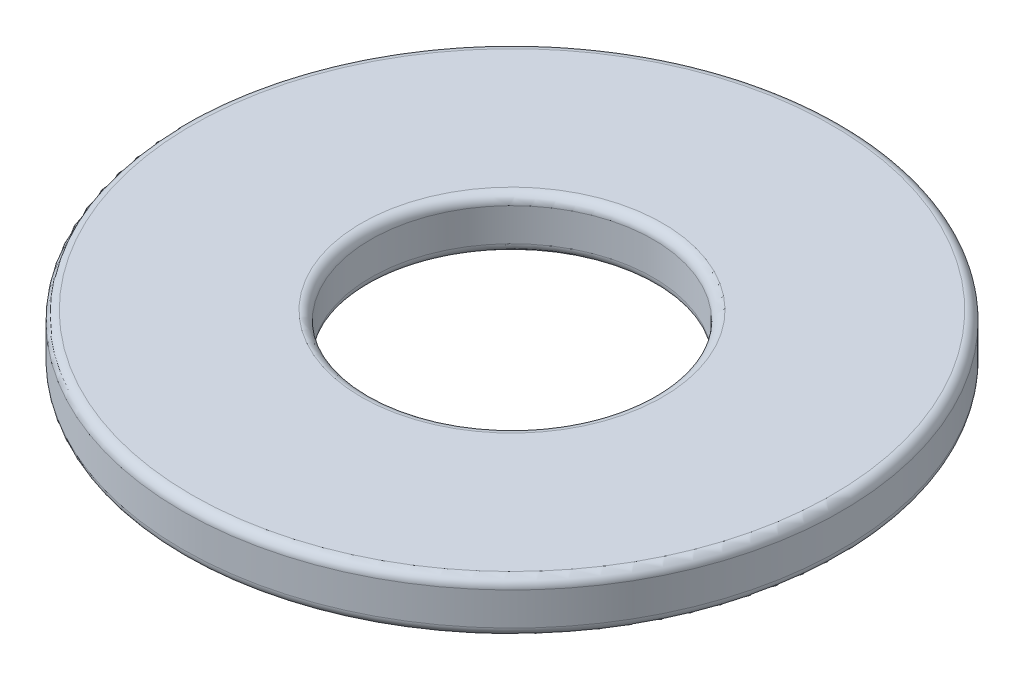
SolidWorks part; units mm, degrees
material "AISI 304"
ref_plane "Front Plane" through (0, 0, 0) normal (0, 0, 1) x (1, 0, 0)
ref_plane "Top Plane" through (0, 0, 0) normal (0, 1, 0) x (1, 0, 0)
ref_plane "Right Plane" through (0, 0, 0) normal (1, 0, 0) x (0, 0, -1)
sketch "Sketch1" plane through (0, 0, 0) normal (0, 1, 0) x (1, 0, 0)
  circle A0 centre (0, 0) radius 3.5
  circle A1 centre (0, 0) radius 1.5
  dimension "D1" = 3
  dimension "D2" = 7
extrude "Boss-Extrude1" add sketch "Sketch1" along normal blind 0.55
fillet "Fillet1" radius 0.1 4 edges at (0, 0, 3.5) (0, 0.55, 3.5) (0, 0, 1.5) (0, 0.55, 1.5)
